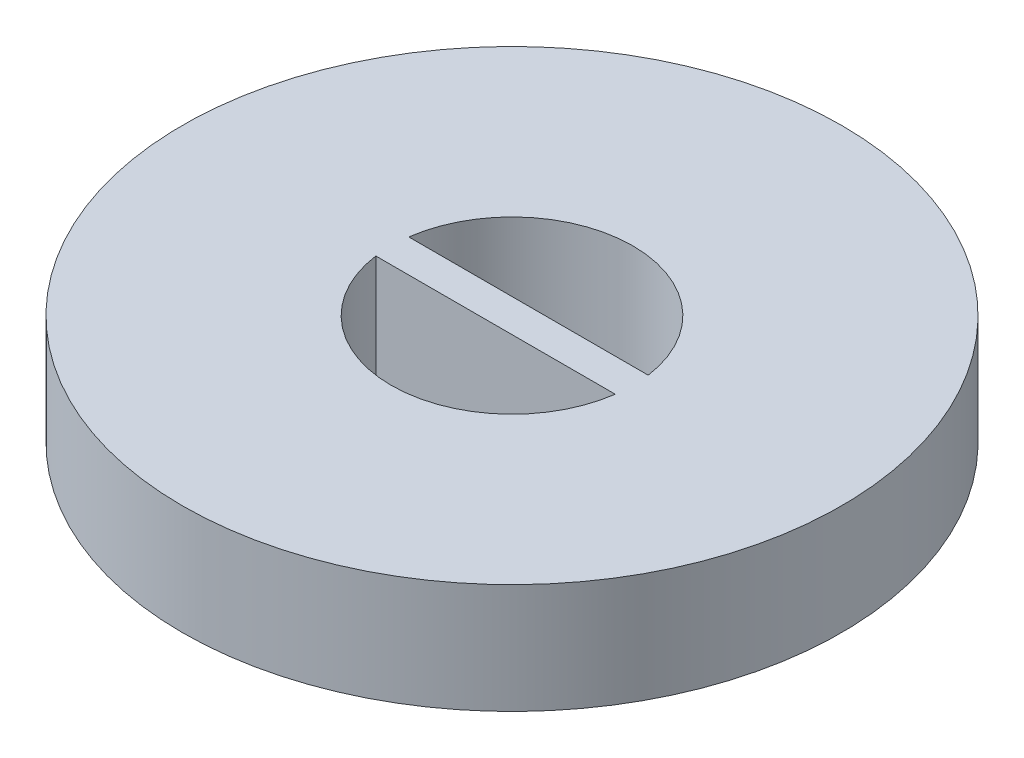
SolidWorks part; units mm, degrees
ref_plane "Front Plane" through (0, 0, 0) normal (0, 0, 1) x (1, 0, 0)
ref_plane "Top Plane" through (0, 0, 0) normal (0, 1, 0) x (1, 0, 0)
ref_plane "Right Plane" through (0, 0, 0) normal (1, 0, 0) x (0, 0, -1)
sketch "Sketch2" plane through (0, 0, 0) normal (0, 1, 0) x (1, 0, 0)
  circle A0 centre (0, 0) radius 6
extrude "Boss-Extrude1" add sketch "Sketch2" along normal blind 2
sketch "Sketch3" plane through (0, 2, 0) normal (0, 1, 0) x (1, 0, 0)
  line L0 (0, 0) -> (0, 0.3)
  line L1 (0, 0) -> (0, -0.3)
  line L2 (0, 0.3) -> (-3.2944, 0.3)
  line L8 (-3.2944, 0.3) -> (3.0683, 0.3)
  line L9 (-3.2944, 0.3) -> (-3.2944, -0.3)
  line L10 (-3.2944, -0.3) -> (3.0683, -0.3)
  line L11 (3.0683, 0.3) -> (3.0683, -0.3)
  circle A0 centre (0, 0) radius 2.2
extrude "Cut-Extrude3" cut sketch "Sketch3" against normal blind 4 contours L8 A0 L2 | L10 A0
